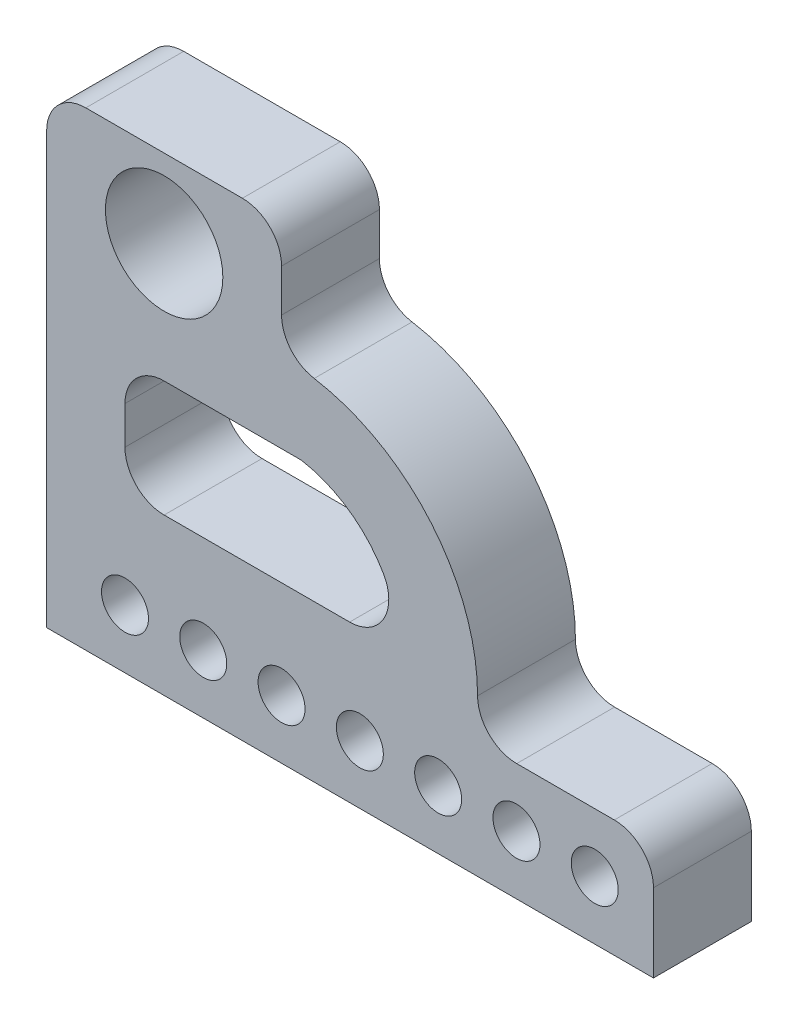
SolidWorks part; units mm, degrees
ref_plane "Front Plane" through (0, 0, 0) normal (0, 0, 1) x (1, 0, 0)
ref_plane "Top Plane" through (0, 0, 0) normal (0, 1, 0) x (1, 0, 0)
ref_plane "Right Plane" through (0, 0, 0) normal (1, 0, 0) x (0, 0, -1)
sketch "Sketch1" plane through (0, 0, 0) normal (0, 0, 1) x (1, 0, 0)
  line L0 (40.0634, -29.9494) -> (64.9995, -29.9552)
  line L2 (-80.0028, -59.9178) -> (-80.0028, 50.0822)
  line L3 (-70.0028, 60.0822) -> (-30.0028, 60.0822)
  line L5 (-20.0028, 50.0822) -> (-20.0028, 39.2431)
  line L6 (-15.0028, 9.6627) -> (-50.0028, 9.6627)
  line L7 (-80.0028, -59.9178) -> (74.9972, -59.9178)
  line L10 (74.9972, -59.9178) -> (74.9972, -39.9552)
  line L11 (-60.0028, -0.3373) -> (-60.0028, -9.9963)
  line L16 (-49.9991, -19.9963) -> (-2.6089, -19.9788)
  circle A0 centre (-50, 40.0822) radius 15
  arc A1 (30.0657, -19.9576) -> (-11.6694, 29.3829) centre (-20.0165, -19.9988) ccw
  arc A2 (-11.6694, 29.3829) -> (-20.0028, 39.2431) centre (-10.0028, 39.2431) cw
  arc A3 (30.0657, -19.9576) -> (40.0634, -29.9494) centre (40.0657, -19.9494) ccw
  arc A6 (-30.0028, 60.0822) -> (-20.0028, 50.0822) centre (-30.0028, 50.0822) cw
  arc A7 (-80.0028, 50.0822) -> (-70.0028, 60.0822) centre (-70.0028, 50.0822) cw
  arc A8 (64.9995, -29.9552) -> (74.9972, -39.9552) centre (64.9972, -39.9552) cw
  arc A9 (6.0537, -4.9893) -> (-15.0028, 9.6627) centre (-20.0165, -19.9988) ccw
  circle A10 centre (-60.0028, -44.9178) radius 6
  circle A11 centre (-40.0028, -44.9178) radius 6
  circle A12 centre (-20.0028, -44.9178) radius 6
  circle A13 centre (-0.0028, -44.9178) radius 6
  circle A14 centre (19.9972, -44.9178) radius 6
  circle A15 centre (39.9972, -44.9178) radius 6
  circle A16 centre (59.9972, -44.9178) radius 6
  arc A17 (10.0658, -19.9741) -> (-15.0028, 9.6627) centre (-20.0165, -19.9988) ccw construction
  arc A18 (6.0537, -4.9893) -> (-2.6089, -19.9788) centre (-2.6126, -9.9788) cw
  arc A19 (-60.0028, -9.9963) -> (-49.9991, -19.9963) centre (-50.0028, -9.9963) ccw
  arc A20 (-60.0028, -0.3373) -> (-50.0028, 9.6627) centre (-50.0028, -0.3373) cw
  point P0 (0, 0)
  point P29 (-20.0028, 60.0822)
  point P32 (-80.0028, 60.0822)
  dimension "D5" = 20
  dimension "D7" = 10
  dimension "D8" = 10
  dimension "D9" = 20
  dimension "D3" = 7
  dimension "D12" = 10
  dimension "D1" = 60
  dimension "D2" = 120
  dimension "D4" = 155
  dimension "D6" = 15
  dimension "D10" = 20
  dimension "D11" = 120
extrude "Boss-Extrude1" add sketch "Sketch1" along normal blind 25
